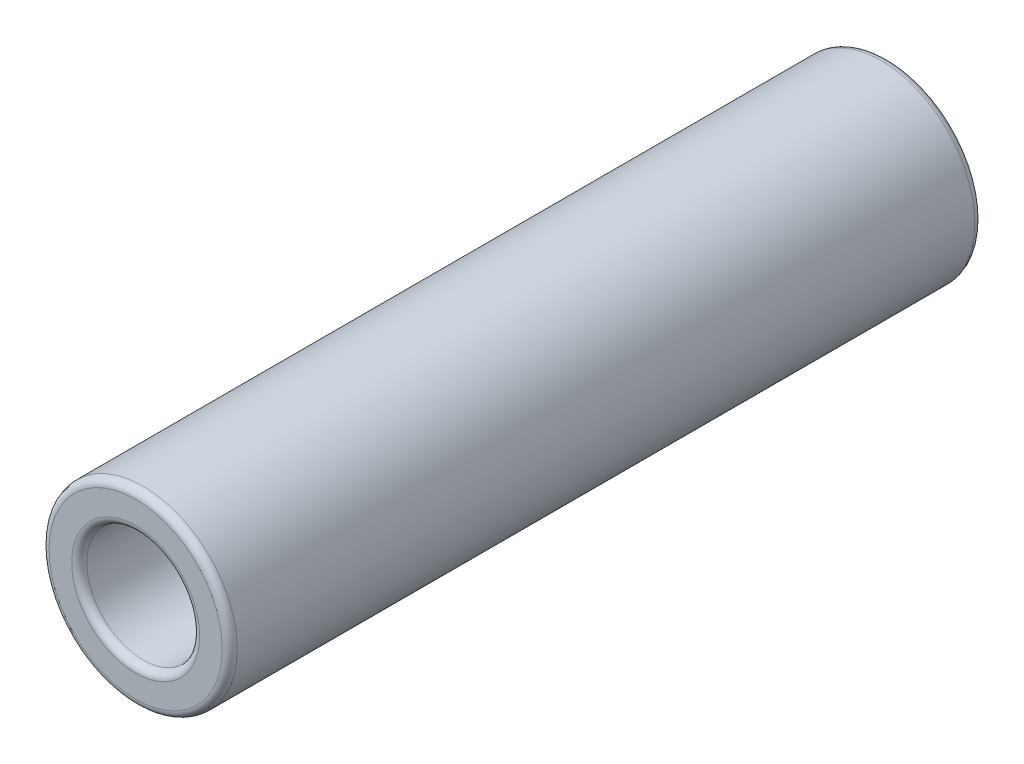
SolidWorks part; units mm, degrees
ref_plane "Front Plane" through (0, 0, 0) normal (0, 0, 1) x (1, 0, 0)
ref_plane "Top Plane" through (0, 0, 0) normal (0, 1, 0) x (1, 0, 0)
ref_plane "Right Plane" through (0, 0, 0) normal (1, 0, 0) x (0, 0, -1)
sketch "Sketch1" plane through (0, 0, 0) normal (0, 0, 1) x (1, 0, 0)
  circle A0 centre (0, 0) radius 6.25
  circle A1 centre (0, 0) radius 3.75
  dimension "D1" = 12.5
  dimension "D2" = 7.5
extrude "Boss-Extrude1" add sketch "Sketch1" along normal blind 50
fillet "Fillet1" radius 0.5 4 edges at (3.75, 0, 0) (6.25, 0, 0) (3.75, 0, 50) (6.25, 0, 50)
ref_plane "Plane1" through (0, 0, 25) normal (0, 0, 1) x (1, 0, 0)
